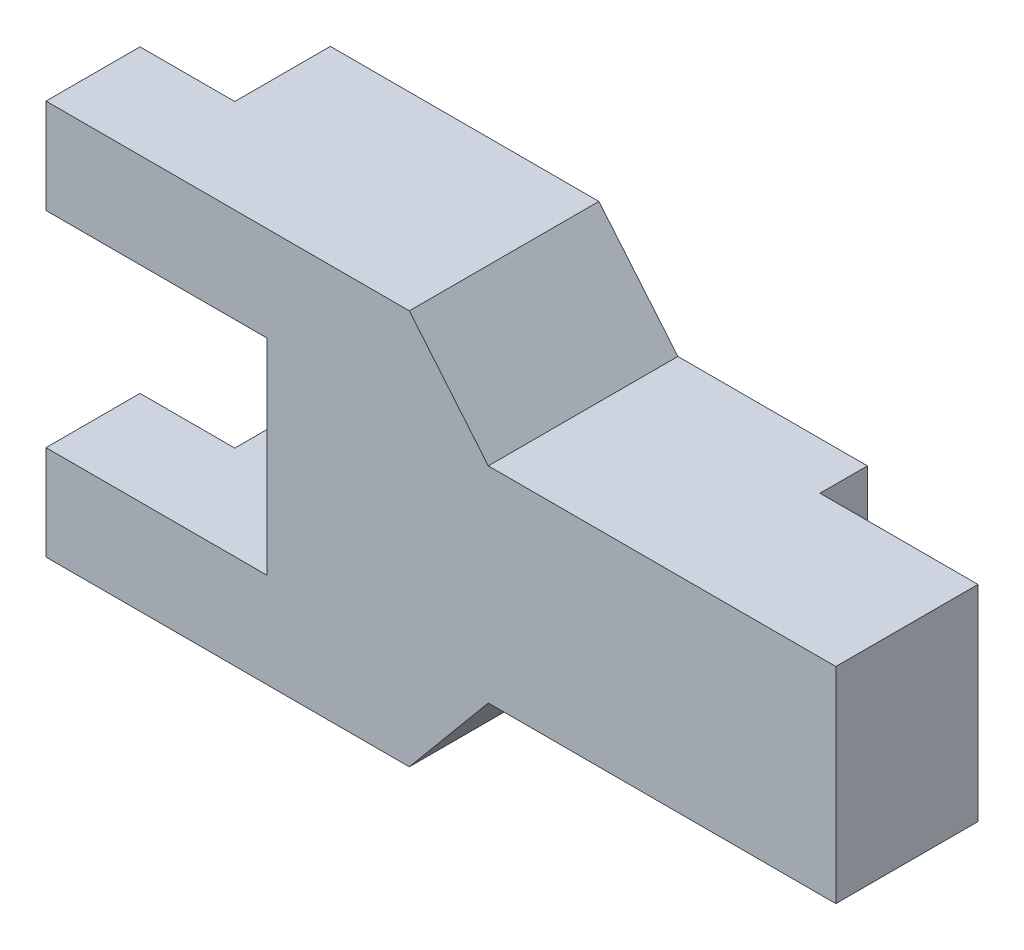
SolidWorks part; units mm, degrees
ref_plane "Ön Düzlem" through (0, 0, 0) normal (0, 0, 1) x (1, 0, 0)
ref_plane "Üst Düzlem" through (0, 0, 0) normal (0, 1, 0) x (1, 0, 0)
ref_plane "Sağ Düzlem" through (0, 0, 0) normal (1, 0, 0) x (0, 0, -1)
sketch "Çizim1" plane through (0, 0, 0) normal (0, 0, 1) x (1, 0, 0)
  line L0 (-283.1761, 779.0061) -> (-1400.7761, 779.0061)
  line L5 (-1400.7761, 779.0061) -> (-1654.7761, 1083.8061)
  line L6 (-1654.7761, 1083.8061) -> (-2823.1761, 1083.8061)
  line L7 (-2823.1761, 1083.8061) -> (-2823.1761, 779.0061)
  line L8 (-2823.1761, 779.0061) -> (-2111.9761, 779.0061)
  line L9 (-2111.9761, 779.0061) -> (-2111.9761, 118.6061)
  line L10 (-2111.9761, 118.6061) -> (-2823.1761, 118.6061)
  line L11 (-2823.1761, 118.6061) -> (-2823.1761, -186.1939)
  line L12 (-2823.1761, -186.1939) -> (-1654.7761, -186.1939)
  line L13 (-1654.7761, -186.1939) -> (-1400.7761, 118.6061)
  line L14 (-1400.7761, 118.6061) -> (-283.1761, 118.6061)
  line L15 (-283.1761, 118.6061) -> (-283.1761, 779.0061)
  dimension "D1" = 304.8
  dimension "D2" = 304.8
  dimension "D3" = 660.4
  dimension "D4" = 660.4
  dimension "D5" = 1117.6
  dimension "D6" = 711.2
  dimension "D7" = 711.2
  dimension "D8" = 1168.4
  dimension "D9" = 1168.4
  dimension "D10" = 254
  dimension "D11" = 254
  dimension "D12" = 304.8
extrude "Yükseklik-Ekstrüzyon3" add sketch "Çizim1" along normal blind 609.6
sketch "Çizim2" plane through (0, 0, 0) normal (0, 0, -1) x (-1, 0, 0)
  line L0 (1400.7761, 118.6061) -> (283.1761, 118.6061) construction
  line L1 (283.1761, 779.0061) -> (791.1761, 779.0061)
  line L2 (283.1761, 779.0061) -> (283.1761, 118.6061)
  line L3 (283.1761, 118.6061) -> (791.1761, 118.6061)
  line L4 (791.1761, 779.0061) -> (791.1761, 118.6061)
  dimension "D1" = 508
extrude "Kes-Ekstrüzyon1" cut sketch "Çizim2" against normal blind 152.4
sketch "Çizim3" plane through (0, 0, 0) normal (0, 0, -1) x (-1, 0, 0)
  line L0 (2111.9761, 118.6061) -> (2823.1761, 118.6061) construction
  line L1 (2823.1761, -186.1939) -> (2518.3761, -186.1939)
  line L2 (2823.1761, -186.1939) -> (2823.1761, 118.6061)
  line L3 (2823.1761, 118.6061) -> (2518.3761, 118.6061)
  line L4 (2518.3761, -186.1939) -> (2518.3761, 118.6061)
  line L5 (1654.7761, 1083.8061) -> (2823.1761, 1083.8061) construction
  line L6 (2823.1761, 779.0061) -> (2518.3761, 779.0061)
  line L7 (2823.1761, 779.0061) -> (2823.1761, 1083.8061)
  line L8 (2823.1761, 1083.8061) -> (2518.3761, 1083.8061)
  line L9 (2518.3761, 779.0061) -> (2518.3761, 1083.8061)
  dimension "D1" = 304.8
  dimension "D2" = 304.8
extrude "Kes-Ekstrüzyon2" cut sketch "Çizim3" against normal blind 307.34 contours L7 L6 L9 L8 | L2 L1 L4 L3
